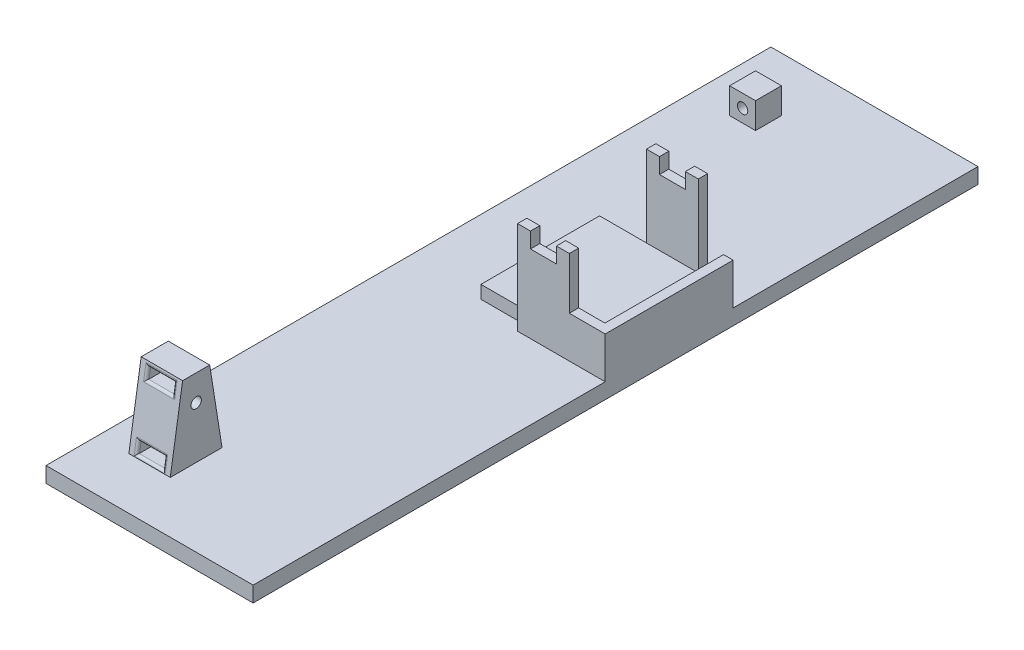
SolidWorks part; units mm, degrees
ref_plane "Front Plane" through (0, 0, 0) normal (0, 0, 1) x (1, 0, 0)
ref_plane "Top Plane" through (0, 0, 0) normal (0, 1, 0) x (1, 0, 0)
ref_plane "Right Plane" through (0, 0, 0) normal (1, 0, 0) x (0, 0, -1)
sketch "Test Mount Sketch" plane through (0, 0, 0) normal (1, 0, 0) x (0, 0, -1)
  line L0 (0, 0) -> (0, 36.029) construction
  line L1 (-5, 0) -> (-2.6163, 15)
  line L8 (-2.6163, 15) -> (2.6163, 15)
  line L9 (2.6163, 15) -> (5, 0)
  line L11 (-5, 0) -> (5, 0)
  circle A0 centre (0, 10) radius 1
  dimension "D4" = 2
  dimension "D6" = 5
  dimension "D5" = 10
extrude "Test Mount Extrude" add sketch "Test Mount Sketch" along normal mid plane 8
sketch "Moutning Plate Sketch" plane through (0, 0, 0) normal (0, 1, 0) x (1, 0, 0)
  line L0 (0, 0) -> (0, 30.7762) construction
  line L1 (4, -5) -> (-4, -5) construction
  line L2 (-10, -15) -> (30, -15)
  line L3 (-10, -15) -> (-10, 125)
  line L4 (-10, 125) -> (30, 125)
  line L5 (30, -15) -> (30, 125)
  line L6 (4, 5) -> (-4, 5) construction
  dimension "D1" = 10
  dimension "D2" = 120
  dimension "D3" = 40
  dimension "D4" = 30
extrude "Mounting Plate Extrude" add sketch "Moutning Plate Sketch" against normal blind 3
sketch "Servo Mount Sketch" plane through (0, 0, 0) normal (0, 1, 0) x (1, 0, 0)
  line L1 (27.95, 55) -> (11.07, 55) construction
  line L3 (28.15, 77.71) -> (30, 77.71)
  line L4 (-10, 125) -> (-10, -15)
  line L5 (-10, -15) -> (30, -15)
  line L6 (30, -15) -> (30, 125)
  line L7 (30, 125) -> (-10, 125)
  line L8 (-10, 125) -> (-10, -15)
  line L9 (-10, -15) -> (30, -15)
  line L10 (30, -15) -> (30, 125)
  line L11 (30, 125) -> (-10, 125)
  line L12 (30, 77.71) -> (30, 53)
  line L13 (30, 53) -> (13.07, 53)
  line L14 (13.07, 53) -> (13.07, 54.8)
  line L15 (11.07, 50.09) -> (11.07, 55) construction
  line L16 (27.95, 77.71) -> (11.07, 77.71) construction
  line L18 (13.07, 77.91) -> (13.07, 79.71)
  line L19 (13.07, 79.71) -> (23.07, 79.71)
  line L20 (23.07, 77.91) -> (23.07, 79.71)
  line L21 (11.07, 77.71) -> (11.07, 82.58) construction
  line L22 (28.15, 77.71) -> (28.15, 54.8)
  line L23 (28.15, 54.8) -> (13.07, 54.8)
  line L24 (27.95, 55) -> (27.95, 77.71) construction
  line L25 (13.07, 77.91) -> (23.07, 77.91)
  dimension "D2" = 0.2
  dimension "D3" = 2
  dimension "D5" = 10
  dimension "D6" = 2
  dimension "D7" = 0.2
  dimension "D8" = 0.2
  dimension "D1" = 0
extrude "Mounting Servo Extrude" add sketch "Servo Mount Sketch" along normal blind 8
sketch "Servo Floor Sketch" plane through (0, 0, 0) normal (0, 1, 0) x (1, 0, 0)
  line L1 (4.2, 77.71) -> (28.15, 77.71)
  line L2 (4.2, 77.71) -> (4.2, 54.8)
  line L3 (4.2, 54.8) -> (28.15, 54.8)
  line L4 (28.15, 77.71) -> (28.15, 54.8)
extrude "Servo Floor Extrude" add sketch "Servo Floor Sketch" along normal blind 2.5
ref_plane "Routing Cut Plane" through (0, 0, 5) normal (0, 0, 1) x (1, 0, 0)
sketch "Routing Holes Sketch" plane through (0, 0, 5) normal (0, 0, 1) x (1, 0, 0)
  line L0 (-4, 11) -> (-4, 9) construction
  line L1 (-4, 11) -> (-4, 9) construction
  line L2 (4, 9) -> (4, 11) construction
  line L3 (4, 9) -> (4, 11) construction
  line L4 (-4, 10) -> (4, 10) construction
  line L5 (0, 0) -> (0, 15) construction
  line L6 (4, 15) -> (-4, 15) construction
  line L7 (4, 0) -> (-4, 0) construction
  line L8 (-2.5, 14) -> (2.5, 14)
  line L9 (-2.5, 14) -> (-2.5, 12)
  line L10 (-2.5, 12) -> (2.5, 12)
  line L11 (2.5, 14) -> (2.5, 12)
  line L12 (-2.5, 2.5) -> (2.5, 2.5)
  line L13 (-2.5, 2.5) -> (-2.5, 0.5)
  line L14 (-2.5, 0.5) -> (2.5, 0.5)
  line L15 (2.5, 2.5) -> (2.5, 0.5)
  dimension "D1" = 2
  dimension "D2" = 1
  dimension "D3" = 5
  dimension "D4" = 2
  dimension "D5" = 5
  dimension "D6" = 0.5
extrude "Routing Holes Extruded Cut" cut sketch "Routing Holes Sketch" against normal blind 10
fillet "Routing Fillets" radius 0.5 16 edges at (2.5, 13, 2.9341) (0, 12, 3.093) (0, 14, 2.7752) (-2.5, 13, 2.9341) (2.5, 1.5, 4.7616) (0, 2.5, 4.6027) (-2.5, 1.5, 4.7616) (0, 0.5, 4.9205) (0, 2.5, -4.6027) (2.5, 1.5, -4.7616) (0, 0.5, -4.9205) (-2.5, 1.5, -4.7616) (-2.5, 13, -2.9341) (0, 14, -2.7752) (2.5, 13, -2.9341) (0, 12, -3.093)
sketch "Tie Off Base" plane through (0, 0, 0) normal (0, 1, 0) x (1, 0, 0)
  line L0 (0, 0) -> (0, 149.8418) construction
  line L2 (-2.5, 114.5343) -> (2.5, 114.5343)
  line L3 (-2.5, 114.5343) -> (-2.5, 109.5343)
  line L4 (-2.5, 109.5343) -> (2.5, 109.5343)
  line L5 (2.5, 114.5343) -> (2.5, 109.5343)
  line L6 (-2.5, 114.5343) -> (2.5, 109.5343) construction
  line L7 (-2.5, 109.5343) -> (2.5, 114.5343) construction
  point P3 (0, 112.0343)
  dimension "D1" = 5
  dimension "D2" = 5
extrude "Tie Off Base Extrude" add sketch "Tie Off Base" along normal blind 5
sketch "Tie Off Base Hole Sketch" plane through (0, 0, -114.5343) normal (0, 0, -1) x (-1, 0, 0)
  line L0 (0, 0) -> (0, 5) construction
  line L1 (-2.5, 5) -> (2.5, 5) construction
  circle A0 centre (0, 2.5) radius 1
  dimension "D1" = 2
extrude "Tie Off Base Hole Extruded Cut" cut sketch "Tie Off Base Hole Sketch" against normal blind 5
sketch "Servo Hold Sketch" plane through (0, 8, 0) normal (0, 1, 0) x (1, 0, 0)
  line L0 (30, 53) -> (13.07, 53) construction
  line L1 (13.07, 79.71) -> (23.07, 79.71)
  line L2 (13.07, 79.71) -> (13.07, 77.91)
  line L3 (13.07, 77.91) -> (23.07, 77.91)
  line L4 (23.07, 79.71) -> (23.07, 77.91)
  line L5 (13.07, 54.8) -> (23.07, 54.8)
  line L6 (13.07, 54.8) -> (13.07, 53)
  line L7 (13.07, 53) -> (23.07, 53)
  line L8 (23.07, 54.8) -> (23.07, 53)
extrude "Servo Hold Extrude" add sketch "Servo Hold Sketch" along normal blind 10
sketch "Servo Holder Cut Out Sketch" plane through (0, 18, 0) normal (0, 1, 0) x (1, 0, 0)
  line L0 (18.07, 79.71) -> (18.07, 53) construction
  line L1 (23.07, 79.71) -> (13.07, 79.71) construction
  line L2 (13.07, 53) -> (23.07, 53) construction
  line L3 (13.07, 77.91) -> (23.07, 77.91) construction
  line L4 (15.57, 79.71) -> (20.57, 79.71)
  line L5 (15.57, 79.71) -> (15.57, 77.91)
  line L6 (15.57, 77.91) -> (20.57, 77.91)
  line L7 (20.57, 79.71) -> (20.57, 77.91)
  line L8 (23.07, 54.8) -> (13.07, 54.8) construction
  line L9 (15.57, 54.8) -> (20.57, 54.8)
  line L10 (15.57, 54.8) -> (15.57, 53)
  line L11 (15.57, 53) -> (20.57, 53)
  line L12 (20.57, 54.8) -> (20.57, 53)
  dimension "D1" = 5
extrude "Servo Holder Cut out Cut" cut sketch "Servo Holder Cut Out Sketch" against normal blind 3
